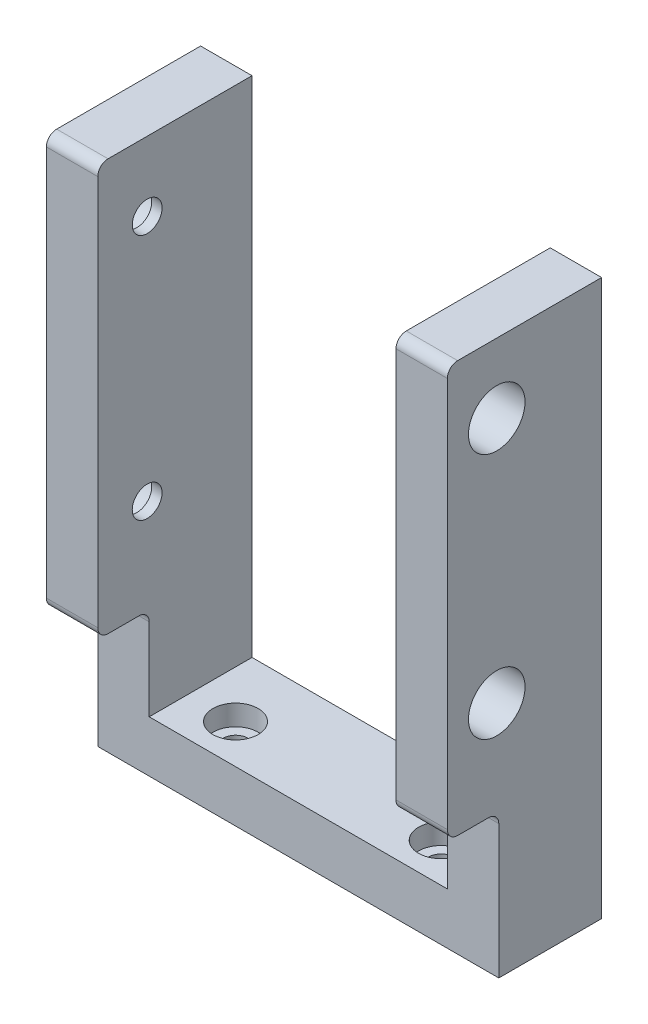
SolidWorks part; units mm, degrees
material "ABS"
ref_plane "Front Plane" through (0, 0, 0) normal (0, 0, 1) x (1, 0, 0)
ref_plane "Top Plane" through (0, 0, 0) normal (0, 1, 0) x (1, 0, 0)
ref_plane "Right Plane" through (0, 0, 0) normal (1, 0, 0) x (0, 0, -1)
sketch "Sketch1" plane through (0, 0, 0) normal (0, 0, 1) x (1, 0, 0)
  line L0 (0, 0) -> (0, 49)
  line L1 (0, 49) -> (-5, 49)
  line L2 (-5, 49) -> (-5, -5)
  line L3 (-5, -5) -> (34, -5)
  line L4 (34, -5) -> (34, 49)
  line L5 (34, 49) -> (29, 49)
  line L6 (29, 49) -> (29, 0)
  line L7 (29, 0) -> (0, 0)
  dimension "D1" = 5
  dimension "D2" = 5
  dimension "D3" = 5
  dimension "D4" = 39
  dimension "D5" = 54
extrude "Boss-Extrude1" add sketch "Sketch1" along normal blind 10
sketch "Sketch2" plane through (0, 0, 10) normal (0, 0, 1) x (1, 0, 0)
  line L0 (0, 0) -> (0, 49) construction
  line L1 (-5, 49) -> (0, 49)
  line L2 (-5, 49) -> (-5, 9)
  line L3 (-5, 9) -> (0, 9)
  line L4 (0, 49) -> (0, 9)
  dimension "D1" = 40
extrude "Boss-Extrude2" add sketch "Sketch2" along normal blind 5
ref_plane "Plane1" through (14.5, 0, 0) normal (-1, 0, 0) x (0, 0, 1)
mirror "Mirror1" about plane through (14.5, 0, 0) normal (-1, 0, 0) of "Boss-Extrude2"
hole_wizard "CBORE for M2 SHCS1" positions "Sketch3" profile "Sketch4" counterbore size "M2" standard "ANSI Metric" end condition up to next
sketch "Sketch3" plane through (0, 0, 0) normal (0, 1, 0) x (1, 0, 0)
  point P0 (24.5956, -6.2)
  point P3 (4.5956, -6.2)
sketch "Sketch4" plane through (24.5956, 0, 6.2) normal (1, 0, 0) x (0, 0, 1)
  line L0 (0, 0) -> (0, 5)
  line L1 (0, 5) -> (1.2, 5)
  line L3 (1.2, 5) -> (1.2, 2)
  line L4 (1.2, 2) -> (2.2, 2)
  line L5 (2.2, 2) -> (2.2, 0)
  line L7 (2.2, 0) -> (0, 0)
  line L11 (0, -6.35) -> (0, 107.95) construction
  dimension "Thru Hole Dia." = 2.4
  dimension "Thru Hole Depth" = 5
  dimension "C'Bore Dia." = 4.4
  dimension "C'Bore Depth" = 2
hole_wizard "CBORE for M2.5 SHCS1" positions "Sketch5" profile "Sketch6" counterbore size "M2.5" standard "ANSI Metric"
sketch "Sketch5" plane through (34, 0, 0) normal (1, 0, 0) x (0, 0, -1)
  point P0 (-10.2, 42.25)
  point P3 (-10.2, 18.25)
sketch "Sketch6" plane through (34, 42.25, 10.2) normal (0, 1, 0) x (0, 0, -1)
  line L0 (0, 0) -> (0, 5)
  line L1 (0, 5) -> (1.45, 5)
  line L3 (1.45, 5) -> (1.45, 4)
  line L4 (1.45, 4) -> (2.75, 4)
  line L5 (2.75, 4) -> (2.75, 0)
  line L7 (2.75, 0) -> (0, 0)
  line L11 (0, -6.35) -> (0, 107.95) construction
  dimension "Thru Hole Dia." = 2.9
  dimension "Thru Hole Depth" = 5
  dimension "C'Bore Dia." = 5.5
  dimension "C'Bore Depth" = 4
hole_wizard "CBORE for M2.5 SHCS2" positions "Sketch7" profile "Sketch8" counterbore size "M2.5" standard "ANSI Metric" end condition up to next
sketch "Sketch7" plane through (-5, 0, 0) normal (-1, 0, 0) x (0, 0, 1)
  point P0 (10.2, 42.25)
  point P3 (10.2, 18.25)
sketch "Sketch8" plane through (-5, 42.25, 10.2) normal (0, 1, 0) x (0, 0, 1)
  line L0 (0, 0) -> (0, 5)
  line L1 (0, 5) -> (1.45, 5)
  line L3 (1.45, 5) -> (1.45, 4)
  line L4 (1.45, 4) -> (2.75, 4)
  line L5 (2.75, 4) -> (2.75, 0)
  line L7 (2.75, 0) -> (0, 0)
  line L11 (0, -6.35) -> (0, 107.95) construction
  dimension "Thru Hole Dia." = 2.9
  dimension "Thru Hole Depth" = 5
  dimension "C'Bore Dia." = 5.5
  dimension "C'Bore Depth" = 4
fillet "Fillet1" radius 1 6 edges at (-2.5, 9, 10) (31.5, 9, 10) (31.5, 9, 15) (-2.5, 9, 15) (-2.5, 49, 15) (31.5, 49, 15)
